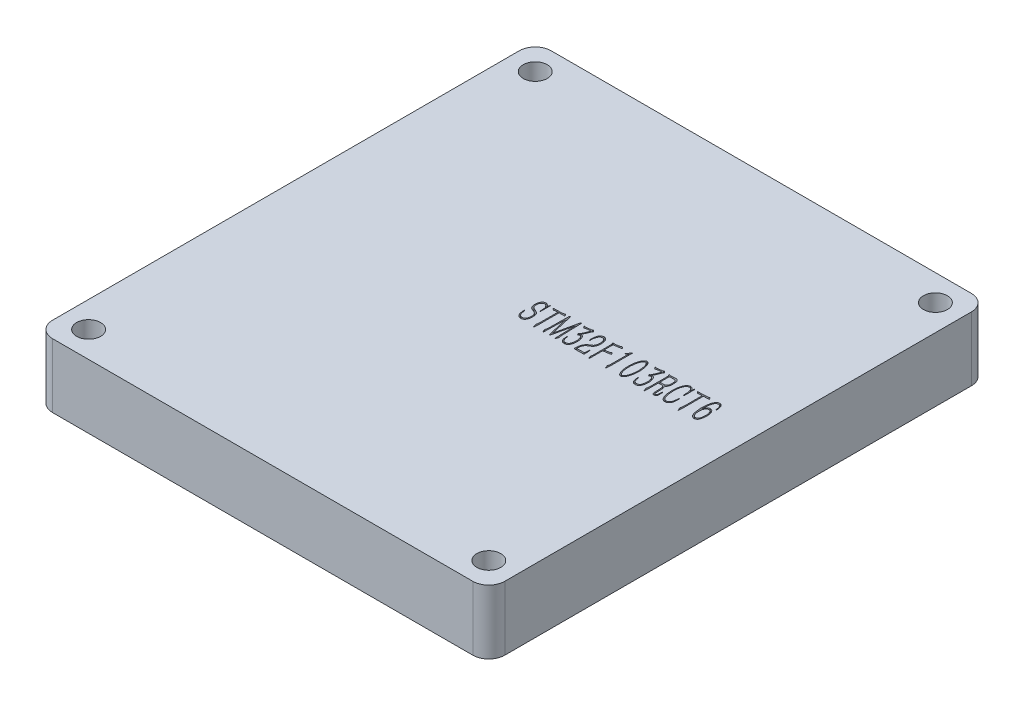
SolidWorks part; units mm, degrees
material "纯金"
ref_plane "前视基准面" through (0, 0, 0) normal (0, 0, 1) x (1, 0, 0)
ref_plane "上视基准面" through (0, 0, 0) normal (0, 1, 0) x (1, 0, 0)
ref_plane "右视基准面" through (0, 0, 0) normal (1, 0, 0) x (0, 0, -1)
sketch "草图1" plane through (0, 0, 0) normal (0, 1, 0) x (1, 0, 0)
  line L1 (-28.25, -31.15) -> (28.25, -31.15)
  line L2 (-28.25, -31.15) -> (-28.25, 31.15)
  line L3 (-28.25, 31.15) -> (28.25, 31.15)
  line L4 (28.25, -31.15) -> (28.25, 31.15)
  line L5 (-28.25, -31.15) -> (28.25, 31.15) construction
  line L6 (-28.25, 31.15) -> (28.25, -31.15) construction
  point P0 (0, 0)
  dimension "D1" = 62.3
  dimension "D2" = 56.5
extrude "凸台-拉伸1" add sketch "草图1" along normal blind 8
sketch "草图2" plane through (0, 8, 0) normal (0, 1, 0) x (1, 0, 0)
  line L0 (28.25, -31.15) -> (28.25, 31.15) construction
  line L1 (-28.25, -31.15) -> (28.25, -31.15) construction
  circle A0 centre (25, -27.9) radius 1.5
  dimension "D1" = 3
  dimension "D2" = 3.25
  dimension "D3" = 3.25
extrude "切除-拉伸1" cut sketch "草图2" against normal through all
ref_plane "基准面1" through (0, 0, 0) normal (0, 0, 1) x (1, 0, 0)
ref_plane "基准面2" through (0, 0, 0) normal (-1, 0, 0) x (0, 0, 1)
mirror "镜向1" about plane through (0, 0, 0) normal (0, 0, 1) of "切除-拉伸1"
mirror "镜向2" about plane through (0, 0, 0) normal (-1, 0, 0) of "镜向1", "切除-拉伸1"
fillet "圆角1" radius 2 4 edges at (-28.25, 4, -31.15) (-28.25, 4, 31.15) (28.25, 4, 31.15) (28.25, 4, -31.15)
sketch "草图3" plane through (0, 8, 0) normal (0, 1, 0) x (1, 0, 0)
  text T0 "STM32F103RCT6"
extrude "切除-拉伸2" cut sketch "草图3" against normal blind 4
